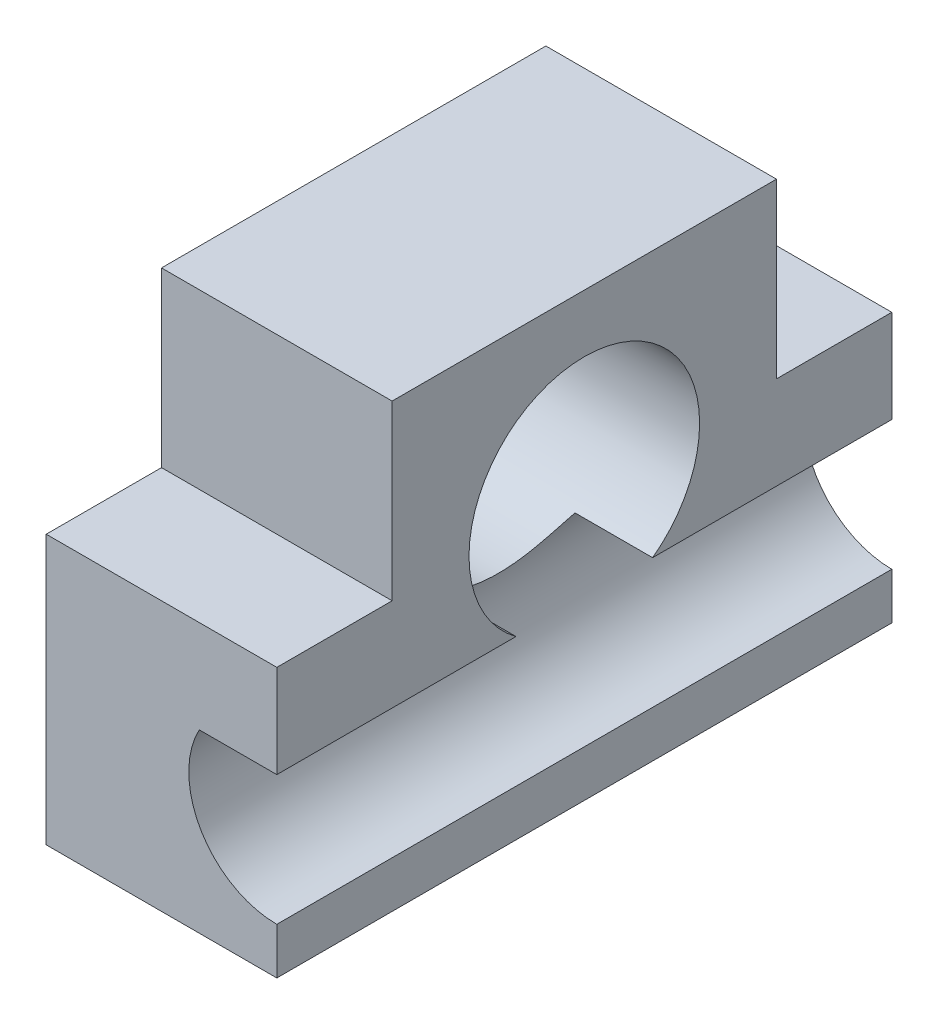
SolidWorks part; units mm, degrees
ref_plane "Front Plane" through (0, 0, 0) normal (0, 0, 1) x (1, 0, 0)
ref_plane "Top Plane" through (0, 0, 0) normal (0, 1, 0) x (1, 0, 0)
ref_plane "Right Plane" through (0, 0, 0) normal (1, 0, 0) x (0, 0, -1)
sketch "Sketch2" plane through (0, 0, 0) normal (0, 0, 1) x (1, 0, 0)
  line L1 (-10.0892, 5.4139) -> (10.0892, 5.4139)
  line L2 (-30, 17.5) -> (30, 17.5)
  line L3 (-30, 17.5) -> (-30, -17.5)
  line L4 (-30, -17.5) -> (30, -17.5)
  line L5 (30, 17.5) -> (30, -17.5)
  line L6 (-30, 17.5) -> (30, -17.5) construction
  line L7 (-30, -17.5) -> (30, 17.5) construction
  arc A0 (-10.0892, 5.4139) -> (10.0892, 5.4139) centre (0, 0) ccw
  point P9 (0, 5.4139)
  dimension "D1" = 22.9
  dimension "D2" = 60
  dimension "D3" = 35
extrude "Boss-Extrude1" add sketch "Sketch2" along normal blind 80
sketch "Sketch3" plane through (30, 0, 0) normal (1, 0, 0) x (0, 0, -1)
  line L0 (-80, -17.5) -> (-80, 17.5) construction
  line L1 (-80, 17.5) -> (0, 17.5) construction
  line L3 (-65, -5) -> (-15, -5)
  line L4 (-65, -5) -> (-65, 40)
  line L5 (-65, 40) -> (-15, 40)
  line L6 (-15, -5) -> (-15, 40)
  line L7 (-65, -5) -> (-15, 40) construction
  line L8 (-65, 40) -> (-15, -5) construction
  circle A0 centre (-40, 17.5) radius 5
  point P0 (-80, 17.5)
  point P1 (-80, 7.5)
  dimension "D2" = 10
  dimension "D1" = 10
  dimension "D3" = 50
  dimension "D4" = 45
extrude "Boss-Extrude2" add sketch "Sketch3" against normal up to surface (60 mm away) up to face at (-30, 0, 40)
sketch "Sketch4" plane through (30, 0, 0) normal (1, 0, 0) x (0, 0, -1)
  line L1 (-45, 17.5) -> (-35, 17.5) construction
  circle A2 centre (-40, 17.5) radius 10.85
  dimension "D1" = 21.7
extrude "Cut-Extrude1" cut sketch "Sketch4" against normal blind 80
sketch "Sketch5" plane through (0, 0, 80) normal (0, 0, 1) x (1, 0, 0)
  line L2 (-10.3006, -5) -> (10.3006, -5)
  line L6 (-10.3006, -5) -> (10.3006, -5)
  line L7 (10.0892, 5.4139) -> (-10.0892, 5.4139)
  line L8 (10.0892, 5.4139) -> (-10.0892, 5.4139)
  arc A2 (10.3006, -5) -> (10.0892, 5.4139) centre (0, 0) ccw
  arc A3 (10.3006, -5) -> (10.0892, 5.4139) centre (0, 0) ccw
  arc A6 (-10.0892, 5.4139) -> (-10.3006, -5) centre (0, 0) ccw
  arc A7 (-10.0892, 5.4139) -> (-10.3006, -5) centre (0, 0) ccw
  dimension "D1" = 0
extrude "Cut-Extrude2" cut sketch "Sketch5" against normal blind 80
sketch "Sketch6" plane through (0, 0, 80) normal (0, 0, 1) x (1, 0, 0)
  line L0 (0, 0) -> (0, 40)
  line L1 (-30, 40) -> (30, 40) construction
  line L2 (0, 40) -> (30, 40)
  line L3 (30, 40) -> (30, -17.5)
  line L4 (30, -17.5) -> (0, -17.5)
  line L5 (-30, -17.5) -> (30, -17.5) construction
  line L6 (0, -17.5) -> (0, 0)
extrude "Cut-Extrude3" cut sketch "Sketch6" against normal blind 80
sketch "Sketch8" plane through (0, 0, 0) normal (1, 0, 0) x (0, 0, -1)
  circle A0 centre (-40, 17.5) radius 15
  dimension "D1" = 30
extrude "Cut-Extrude5" cut sketch "Sketch8" against normal blind 25
